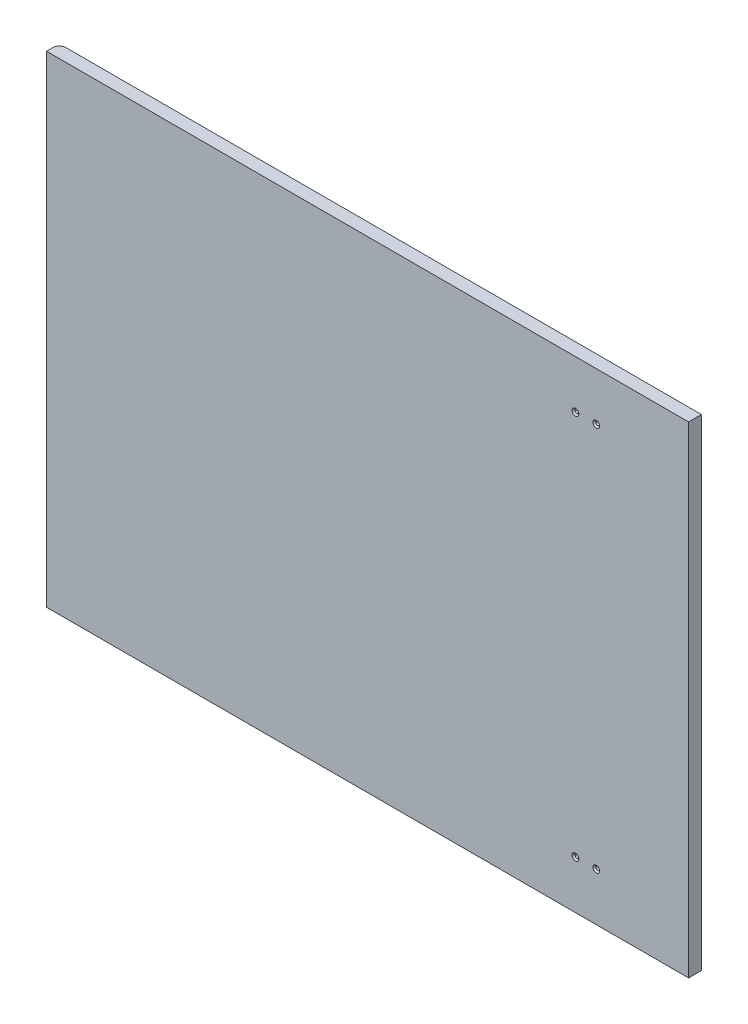
SolidWorks part; units mm, degrees
ref_plane "Front Plane" through (0, 0, 0) normal (0, 0, 1) x (1, 0, 0)
ref_plane "Top Plane" through (0, 0, 0) normal (0, 1, 0) x (1, 0, 0)
ref_plane "Right Plane" through (0, 0, 0) normal (1, 0, 0) x (0, 0, -1)
other "Bounding Box"
ref_plane "Default Plane" through (-400, -300, 0) normal (0, 1, 0) x (1, 0, 0)
sketch "Sketch1" plane through (0, 0, 0) normal (0, 0, 1) x (1, 0, 0)
  line L1 (-400, -300) -> (400, -300)
  line L2 (-400, -300) -> (-400, 300)
  line L3 (-400, 300) -> (400, 300)
  line L4 (400, -300) -> (400, 300)
  line L5 (-400, -300) -> (400, 300) construction
  line L6 (-400, 300) -> (400, -300) construction
  point P0 (0, 0)
  dimension "D1" = 800
  dimension "D2" = 600
extrude "Boss-Extrude1" add sketch "Sketch1" along normal blind 16
hole_wizard "CSK for #8 Flat Head Machine Screw (100)1" positions "Sketch4" profile "Sketch3" countersink size "#8" standard "ANSI Inch"
sketch "Sketch4" plane through (0, 0, 16) normal (0, 0, 1) x (1, 0, 0)
  line L0 (259, -240) -> (285, -240) construction
  line L2 (-400, -300) -> (400, -300) construction
  line L3 (400, -300) -> (400, 300) construction
  point P0 (285, -240)
  point P2 (259, -240)
  dimension "D1" = 60
  dimension "D2" = 115
  dimension "D3" = 26
sketch "Sketch3" plane through (285, -240, 16) normal (1, 0, 0) x (0, -1, 0)
  line L0 (0, 0) -> (0, 26.3507)
  line L1 (0, 26.3507) -> (2.2479, 25)
  line L2 (2.2479, 25) -> (2.2479, 1.6518)
  line L3 (2.2479, 1.6518) -> (4.2164, 0)
  line L5 (4.2164, 0) -> (0, 0)
  line L6 (-2.2479, 1.6518) -> (-4.2164, 0) construction
  line L10 (0, 26.3507) -> (-2.2479, 25) construction
  line L11 (0, -6.35) -> (0, 107.95) construction
  dimension "Hole Dia." = 4.4958
  dimension "Hole Depth" = 25
  dimension "Near C'Sink Dia." = 8.4328
  dimension "Near C'Sink Angle" = 100
  dimension "Drill Angle" = 118
mirror "Mirror1" about plane through (0, 0, 0) normal (0, 1, 0) of "CSK for #8 Flat Head Machine Screw (100)1"
fillet "Fillet1" radius 8 1 edges at (-400, 0, 0)
